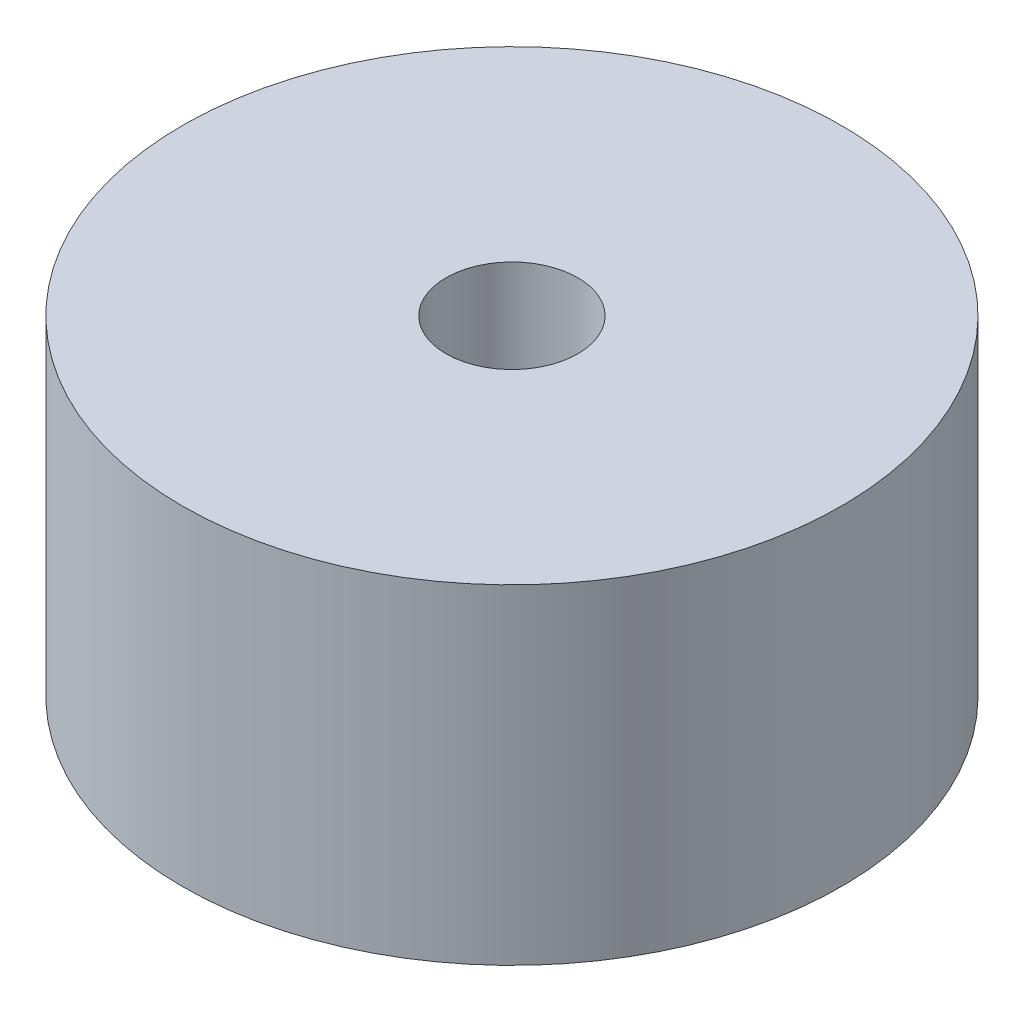
SolidWorks part; units mm, degrees
ref_plane "Front Plane" through (0, 0, 0) normal (0, 0, 1) x (1, 0, 0)
ref_plane "Top Plane" through (0, 0, 0) normal (0, 1, 0) x (1, 0, 0)
ref_plane "Right Plane" through (0, 0, 0) normal (1, 0, 0) x (0, 0, -1)
sketch "Sketch1" plane through (0, 0, 0) normal (0, 1, 0) x (1, 0, 0)
  circle A0 centre (0, 0) radius 0.5
  circle A1 centre (0, 0) radius 2.5
  point P5 (-0.7273, 1.8169)
  point P10 (-0.48, 1.8601)
  point P12 (-0.4961, 1.938)
  point P13 (-0.2234, 2)
  dimension "D1" = 1
  dimension "D2" = 5
extrude "Boss-Extrude1" add sketch "Sketch1" along normal blind 2.5
